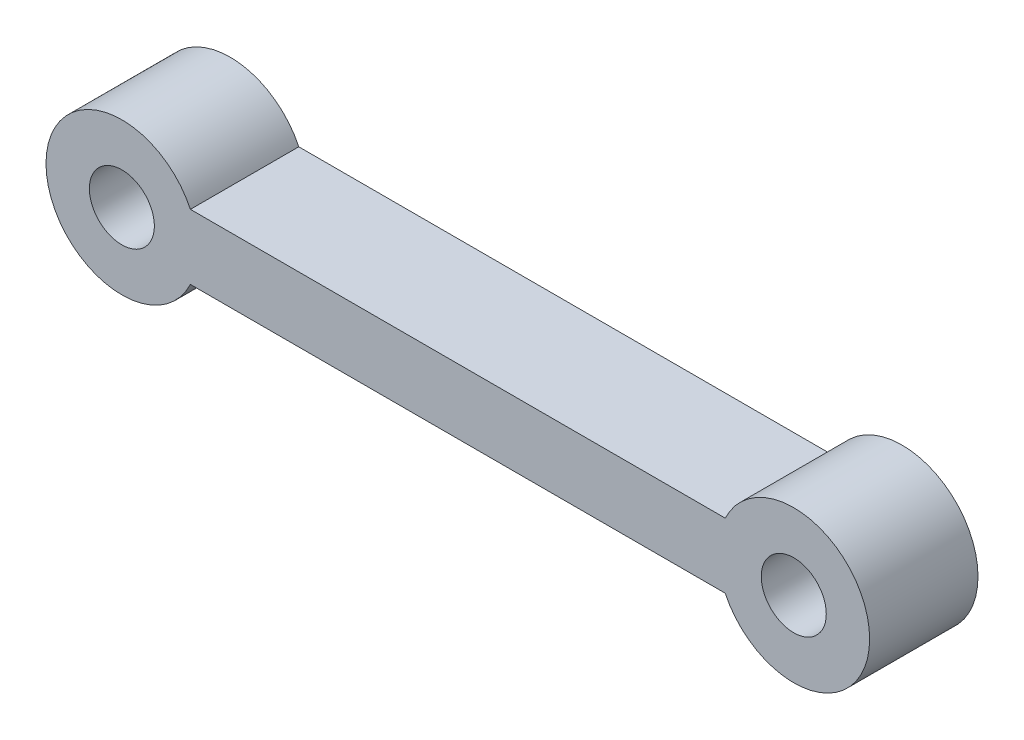
SolidWorks part; units mm, degrees
material "아크릴(내충격성)"
ref_plane "정면" through (0, 0, 0) normal (0, 0, 1) x (1, 0, 0)
ref_plane "윗면" through (0, 0, 0) normal (0, 1, 0) x (1, 0, 0)
ref_plane "우측면" through (0, 0, 0) normal (1, 0, 0) x (0, 0, -1)
sketch "스케치1" plane through (0, 0, 0) normal (0, 0, 1) x (1, 0, 0)
  line L0 (0, 0) -> (31, 0) construction
  line L1 (0, 3.5) -> (31, 3.5)
  line L2 (0, -3.5) -> (31, -3.5)
  line L4 (3.1623, 1.5) -> (27.8377, 1.5)
  line L5 (3.1623, 1.5) -> (3.1623, -1.5)
  line L6 (3.1623, -1.5) -> (27.8377, -1.5)
  line L7 (27.8377, 1.5) -> (27.8377, -1.5)
  line L8 (3.1623, 1.5) -> (27.8377, -1.5) construction
  line L9 (3.1623, -1.5) -> (27.8377, 1.5) construction
  arc A0 (0, 3.5) -> (0, -3.5) centre (0, 0) ccw
  arc A1 (31, -3.5) -> (31, 3.5) centre (31, 0) ccw
  circle A2 centre (0, 0) radius 1.5
  circle A3 centre (31, 0) radius 1.5
  circle A4 centre (0, 0) radius 3.5
  circle A5 centre (31, 0) radius 3.5
  point P3 (15.5, 0)
  point P14 (15.5, 0)
  dimension "D2" = 7
  dimension "D3" = 3
  dimension "D1" = 31
  dimension "D4" = 3
extrude "보스-돌출1" add sketch "스케치1" along normal blind 5 contours A5 L4 A4 L6 | L5 A4 A0 A2 | A1 A5 L7 A3 | L5 A4 | L7 A5
